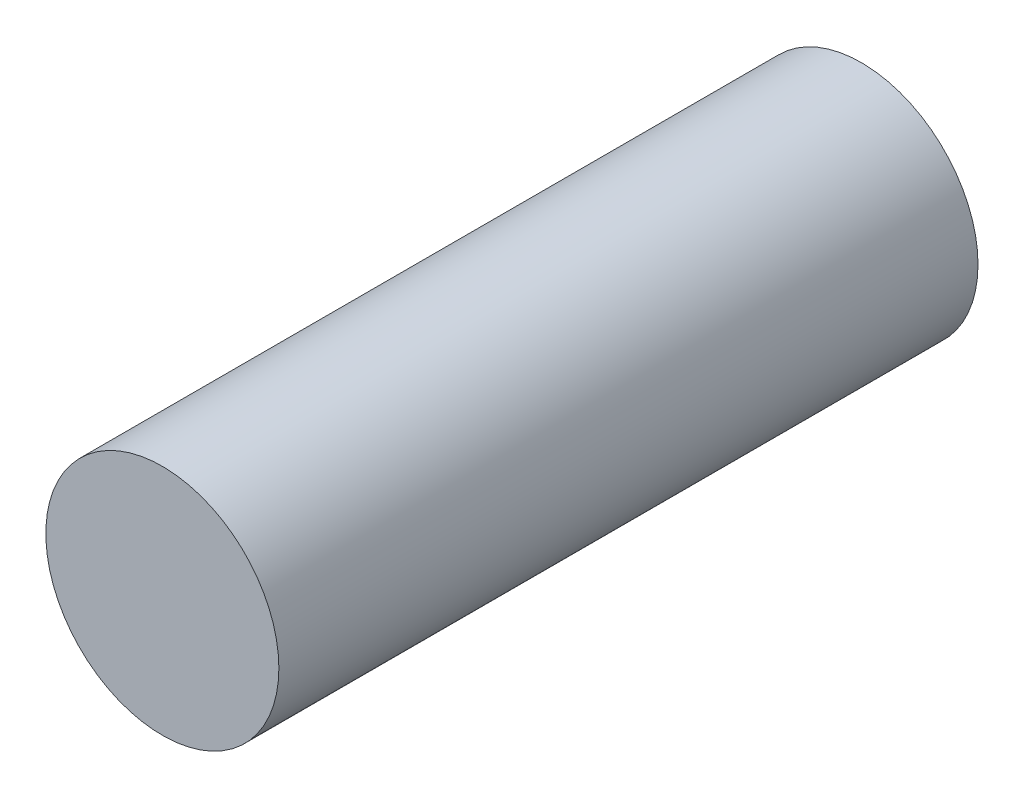
SolidWorks part; units mm, degrees
ref_plane "前视基准面" through (0, 0, 0) normal (0, 0, 1) x (1, 0, 0)
ref_plane "上视基准面" through (0, 0, 0) normal (0, 1, 0) x (1, 0, 0)
ref_plane "右视基准面" through (0, 0, 0) normal (1, 0, 0) x (0, 0, -1)
other "Configuration Table"
sketch "草图1" plane through (0, 0, 0) normal (0, 0, 1) x (1, 0, 0)
  circle A0 centre (0, 0) radius 10
  dimension "D1" = 20
extrude "凸台-拉伸1" add sketch "草图1" along normal blind 60
